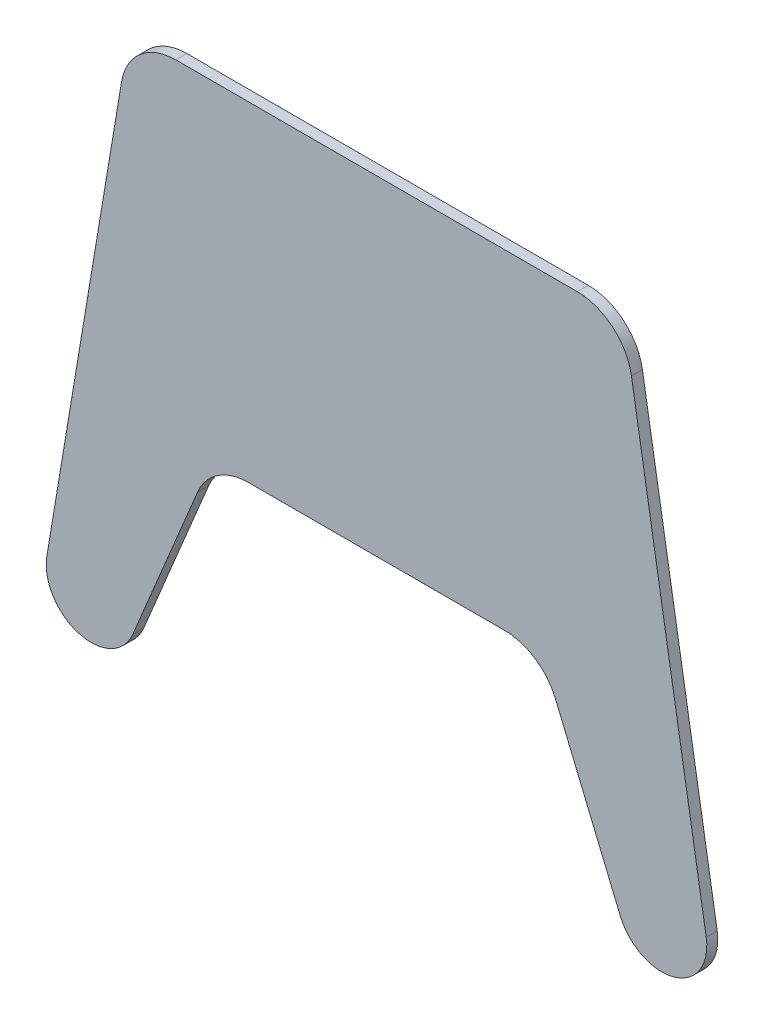
SolidWorks part; units mm, degrees
ref_plane "Front Plane" through (0, 0, 0) normal (0, 0, 1) x (1, 0, 0)
ref_plane "Top Plane" through (0, 0, 0) normal (0, 1, 0) x (1, 0, 0)
ref_plane "Right Plane" through (0, 0, 0) normal (1, 0, 0) x (0, 0, -1)
sketch "Sketch1" plane through (0, 0, 0) normal (0, 0, 1) x (1, 0, 0)
  line L0 (-58.9187, 27.4879) -> (-76.2, -76.2)
  line L3 (-46.3915, 38.1) -> (46.3915, 38.1)
  line L5 (0, 38.1) -> (0, -38.1) construction
  line L6 (-56.3527, -81.9065) -> (-53.975, -76.2)
  line L7 (-76.2, -76.2) -> (-53.975, -76.2) construction
  line L8 (-53.975, -76.2) -> (-41.3564, -45.9154)
  line L9 (58.9187, 27.4879) -> (76.2, -76.2)
  line L10 (76.2, -76.2) -> (53.975, -76.2) construction
  line L11 (53.975, -76.2) -> (41.3564, -45.9154)
  line L12 (-29.6333, -38.1) -> (29.6333, -38.1)
  line L13 (56.3527, -81.9065) -> (53.975, -76.2)
  line L14 (41.6415, 31.075) -> (51.1415, 19.725) construction
  line L15 (-41.6415, 19.725) -> (-51.1415, 19.725) construction
  line L16 (-41.6415, 19.725) -> (-41.6415, 31.075) construction
  line L17 (-41.6415, 31.075) -> (-51.1415, 31.075) construction
  line L18 (-51.1415, 19.725) -> (-51.1415, 31.075) construction
  line L19 (-41.6415, 19.725) -> (-51.1415, 31.075) construction
  line L20 (-41.6415, 31.075) -> (-51.1415, 19.725) construction
  line L21 (41.6415, 19.725) -> (51.1415, 31.075) construction
  line L22 (51.1415, 19.725) -> (51.1415, 31.075) construction
  line L23 (41.6415, 31.075) -> (51.1415, 31.075) construction
  line L24 (41.6415, 19.725) -> (41.6415, 31.075) construction
  line L25 (41.6415, 19.725) -> (51.1415, 19.725) construction
  line L26 (-46.3915, 25.4) -> (46.3915, 25.4) construction
  line L27 (-5.55, 28.5) -> (5.55, 28.5) construction
  line L28 (-5.55, 28.5) -> (-5.55, 22.3) construction
  line L29 (-5.55, 22.3) -> (5.55, 22.3) construction
  line L30 (5.55, 28.5) -> (5.55, 22.3) construction
  line L31 (-5.55, 28.5) -> (5.55, 22.3) construction
  line L32 (-5.55, 22.3) -> (5.55, 28.5) construction
  line L33 (-29.65, 23.834) -> (-29.65, 26.966) construction
  line L34 (29.65, 23.834) -> (29.65, 26.966) construction
  line L36 (-23.3, 27.45) -> (-11.9, 27.45) construction
  line L37 (-23.3, 27.45) -> (-23.3, 23.35) construction
  line L38 (-23.3, 23.35) -> (-11.9, 23.35) construction
  line L39 (-11.9, 27.45) -> (-11.9, 23.35) construction
  line L40 (-23.3, 27.45) -> (-11.9, 23.35) construction
  line L41 (-23.3, 23.35) -> (-11.9, 27.45) construction
  line L45 (23.3, 23.35) -> (11.9, 27.45) construction
  line L46 (23.3, 27.45) -> (11.9, 23.35) construction
  line L47 (11.9, 27.45) -> (11.9, 23.35) construction
  line L48 (23.3, 23.35) -> (11.9, 23.35) construction
  line L49 (23.3, 27.45) -> (23.3, 23.35) construction
  line L50 (23.3, 27.45) -> (11.9, 27.45) construction
  line L51 (-29.65, 23.834) -> (-23.3, 23.834) construction
  line L52 (-11.9, 23.834) -> (-5.55, 23.834) construction
  arc A0 (-76.2, -76.2) -> (-56.3527, -81.9065) centre (-65.9473, -77.9088) ccw
  arc A1 (76.2, -76.2) -> (56.3527, -81.9065) centre (65.9473, -77.9088) cw
  arc A2 (46.3915, 38.1) -> (58.9187, 27.4879) centre (46.3915, 25.4) cw
  arc A3 (-58.9187, 27.4879) -> (-46.3915, 38.1) centre (-46.3915, 25.4) cw
  arc A4 (41.3564, -45.9154) -> (29.6333, -38.1) centre (29.6333, -50.8) ccw
  arc A5 (-41.3564, -45.9154) -> (-29.6333, -38.1) centre (-29.6333, -50.8) cw
  arc A6 (-29.65, 26.966) -> (-29.65, 23.834) centre (-32.15, 25.4) ccw construction
  arc A7 (-29.65, 23.834) -> (-29.65, 26.966) centre (-32.15, 25.4) ccw construction
  arc A8 (-29.65, 23.834) -> (-29.65, 26.966) centre (-32.15, 25.4) ccw construction
  arc A9 (29.65, 23.834) -> (29.65, 26.966) centre (32.15, 25.4) cw construction
  arc A10 (29.65, 23.834) -> (29.65, 26.966) centre (32.15, 25.4) cw construction
  arc A11 (29.65, 26.966) -> (29.65, 23.834) centre (32.15, 25.4) cw construction
  point P0 (0, 0)
  point P18 (57.15, 38.1)
  point P21 (-57.15, 38.1)
  point P26 (-46.3915, 25.4)
  point P31 (46.3915, 25.4)
  point P35 (38.1, -38.1)
  point P38 (-38.1, -38.1)
  point P39 (0, 25.4)
  point P50 (-17.6, 25.4)
  point P66 (17.6, 25.4)
  point P70 (-17.4418, 25.4)
  dimension "D7" = 12.7
  dimension "D10" = 12.7
  dimension "D13" = 5.9
  dimension "D1" = 114.3
  dimension "D2" = 76.2
  dimension "D3" = 152.4
  dimension "D4" = 114.3
  dimension "D5" = 76.2
  dimension "D6" = 22.225
  dimension "D8" = 9.5
  dimension "D9" = 11.35
  dimension "D11" = 11.1
  dimension "D12" = 6.2
  dimension "D14" = 2.5
  dimension "D15" = 11.4
  dimension "D16" = 4.1
  dimension "D17" = 6.35
extrude "Boss-Extrude1" add sketch "Sketch1" along normal blind 2.54
